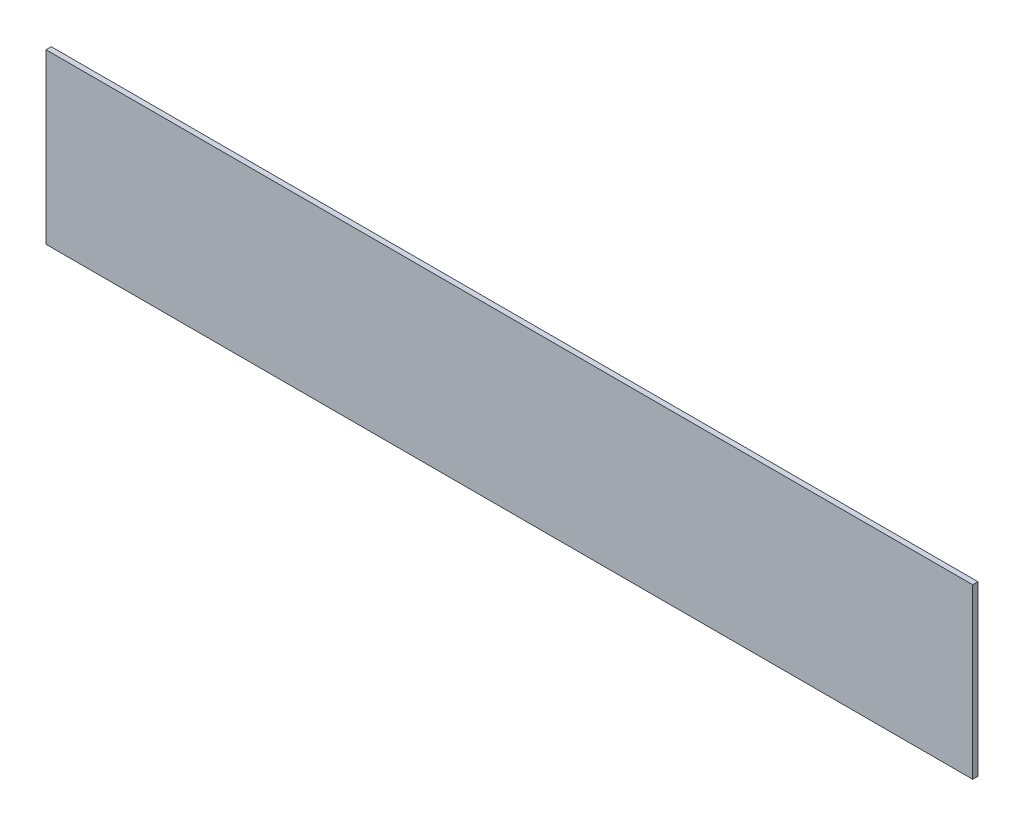
SolidWorks part; units mm, degrees
ref_plane "Front Plane" through (0, 0, 0) normal (0, 0, 1) x (1, 0, 0)
ref_plane "Top Plane" through (0, 0, 0) normal (0, 1, 0) x (1, 0, 0)
ref_plane "Right Plane" through (0, 0, 0) normal (1, 0, 0) x (0, 0, -1)
sketch "Sketch2" plane through (0, 0, 0) normal (0, 0, 1) x (1, 0, 0)
  line L0 (0, 0) -> (0, 50.8)
  line L1 (0, 50.8) -> (279.4, 50.8)
  line L2 (0, 0) -> (279.4, 0)
  line L3 (279.4, 0) -> (279.4, 50.8)
  dimension "D1" = 279.4
  dimension "D2" = 50.8
extrude "Boss-Extrude1" add sketch "Sketch2" along normal blind 1.5875
